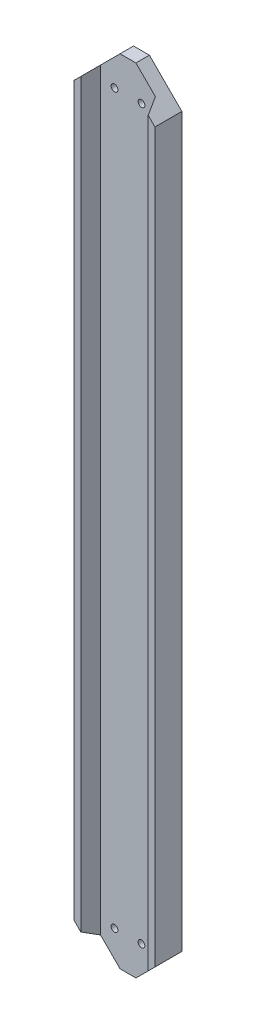
SolidWorks part; units mm, degrees
ref_plane "정면" through (0, 0, 0) normal (0, 0, 1) x (1, 0, 0)
ref_plane "윗면" through (0, 0, 0) normal (0, 1, 0) x (1, 0, 0)
ref_plane "우측면" through (0, 0, 0) normal (1, 0, 0) x (0, 0, -1)
sketch "스케치1" plane through (0, 0, 0) normal (0, 0, 1) x (1, 0, 0)
  line L0 (0, 0) -> (-30, 0)
  line L1 (-30, 0) -> (-30, 2.5)
  line L2 (0, 0) -> (0, 2.5)
  line L3 (0, 2.5) -> (-12.05, 14.55)
  line L4 (-12.05, 14.55) -> (-17.95, 14.55)
  line L5 (-30, 2.5) -> (-17.95, 14.55)
  dimension "D1" = 2.5
  dimension "D2" = 30
  dimension "D3" = 2.5
  dimension "D4" = 5.9
  dimension "D5" = 135
extrude "보스-돌출1" add sketch "스케치1" along normal blind 10 contours L5 L4 L3 L2 L0 L1
sketch "스케치2" plane through (0, 0, 0) normal (0, -1, 0) x (1, 0, 0)
  line L1 (-30, 10) -> (0, 10)
  line L2 (-30, 10) -> (-30, 0)
  line L3 (-30, 0) -> (0, 0)
  line L4 (0, 10) -> (0, 0)
extrude "보스-돌출2" add sketch "스케치2" along normal blind 267.5
ref_plane "평면1" through (0, 2.5, 0) normal (0, -1, 0) x (-1, 0, 0)
ref_plane "평면4" through (0, -132.5, 0) normal (0, -1, 0) x (-1, 0, 0)
mirror "대칭 복사1" about plane through (0, -132.5, 0) normal (0, -1, 0) of "보스-돌출1"
sketch "스케치3" plane through (0, 0, 10) normal (0, 0, 1) x (1, 0, 0)
  line L1 (-27.5, 14.55) -> (-2.5, 14.55)
  line L2 (-27.5, 14.55) -> (-27.5, -294.55)
  line L3 (-27.5, -294.55) -> (-2.5, -294.55)
  line L4 (-2.5, 14.55) -> (-2.5, -294.55)
  line L5 (-30, -267.5) -> (-30, 2.5) construction
  dimension "D1" = 25
  dimension "D2" = 2.5
extrude "컷-돌출1" cut sketch "스케치3" against normal blind 5 draft 25 contours L2 L3 L4 L1
sketch "스케치4" plane through (0, -279.55, 0) normal (0, -1, 0) x (1, 0, 0)
  line L0 (-27.5, 10) -> (-2.5, 10)
  line L1 (-2.5, 10) -> (-14.35, 5)
  line L2 (-14.35, 5) -> (-25.2, 5)
  line L3 (-25.2, 5) -> (-27.5, 10)
  line L5 (-12.05, 5) -> (-12.05, 0) construction
  dimension "D1" = 2.3
  dimension "D2" = 2.3
  dimension "D3" = 5
extrude "컷-돌출2" cut sketch "스케치4" against normal through all
sketch "스케치5" plane through (0, 0, 10) normal (0, 0, 1) x (1, 0, 0)
  line L0 (-30, -267.5) -> (-30, 2.5) construction
  line L1 (-12.05, 14.55) -> (-17.95, 14.55) construction
  line L2 (0, -267.5) -> (0, 2.5) construction
  circle A0 centre (-10, 2.55) radius 1.25
  circle A1 centre (-20, 2.55) radius 1.25
  dimension "D1" = 2.5
  dimension "D2" = 2.5
  dimension "D3" = 10
  dimension "D4" = 12
  dimension "D5" = 10
  dimension "D6" = 12
extrude "컷-돌출3" cut sketch "스케치5" against normal blind 10
mirror "대칭 복사2" about plane through (0, -132.5, 0) normal (0, -1, 0) of "컷-돌출3"
sketch "스케치6" plane through (0, -279.55, 0) normal (0, -1, 0) x (1, 0, 0)
  line L0 (-17.95, 5) -> (-25.2, 5) construction
  line L1 (-25.2, 5) -> (-4.8315, 5)
  line L2 (-25.2, 5) -> (-25.2, 11.6605)
  line L3 (-25.2, 11.6605) -> (-4.8315, 11.6605)
  line L4 (-4.8315, 5) -> (-4.8315, 11.6605)
  dimension "D1" = 0
  dimension "D2" = 0
extrude "컷-돌출4" cut sketch "스케치6" against normal blind 400
ref_plane "평면6" through (0, -267.5, 0) normal (0, -1, 0) x (-1, 0, 0)
